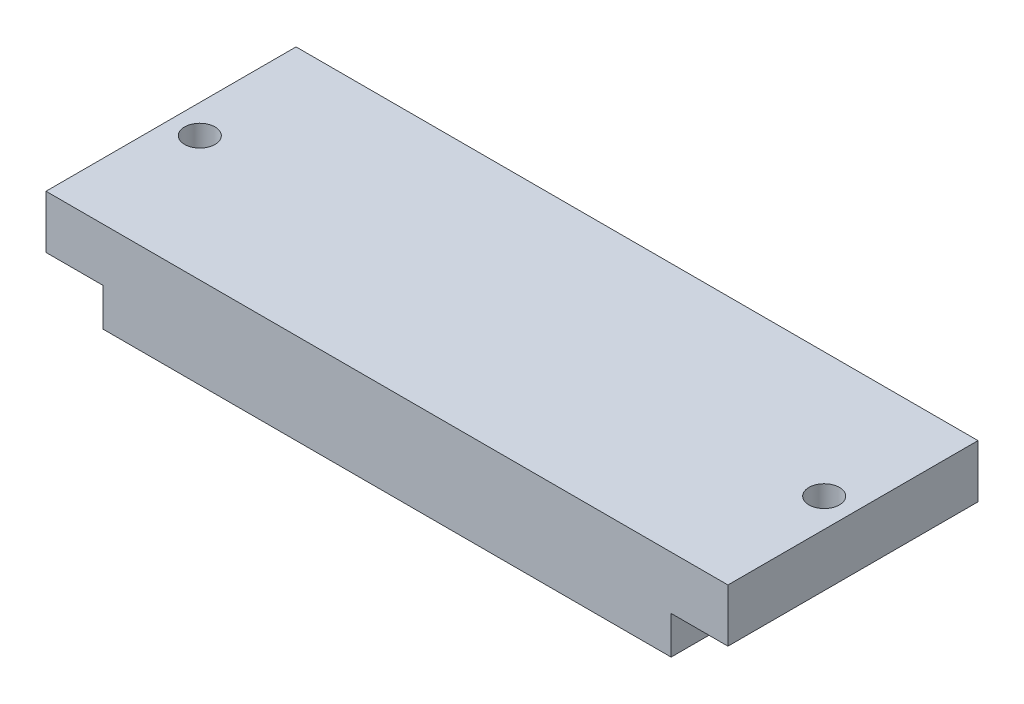
SolidWorks part; units mm, degrees
material "ABS"
ref_plane "Front Plane" through (0, 0, 0) normal (0, 0, 1) x (1, 0, 0)
ref_plane "Top Plane" through (0, 0, 0) normal (0, 1, 0) x (1, 0, 0)
ref_plane "Right Plane" through (0, 0, 0) normal (1, 0, 0) x (0, 0, -1)
sketch "Sketch1" plane through (0, 0, 0) normal (0, 0, 1) x (1, 0, 0)
  line L0 (0, 0) -> (114.3, 0)
  line L1 (0, 0) -> (0, -8.89)
  line L2 (0, -8.89) -> (9.525, -8.89)
  line L3 (114.3, 0) -> (114.3, -8.89)
  line L4 (114.3, -8.89) -> (104.775, -8.89)
  line L5 (9.525, -8.89) -> (9.525, -15.24)
  line L6 (104.775, -8.89) -> (104.775, -15.24)
  line L7 (9.525, -15.24) -> (104.775, -15.24)
  dimension "D1" = 6.35
  dimension "D2" = 8.89
  dimension "D3" = 9.525
  dimension "D4" = 95.25
extrude "Boss-Extrude1" add sketch "Sketch1" along normal blind 41.91
hole_wizard "#10 Clearance Hole1" positions "3DSketch2" profile "Sketch3" hole size "#10" standard "Ansi Inch" end condition through all
sketch3d "3DSketch2"
  line L0 (4.826, 0, 0) -> (4.826, 0, 41.91) construction
  line L1 (114.3, 0, 0) -> (0, 0, 0) construction
  line L2 (114.3, 0, 41.91) -> (0, 0, 41.91) construction
  line L3 (0, 0, 41.91) -> (0, 0, 0) construction
  line L4 (109.474, 0, 0) -> (109.474, 0, 41.91) construction
  line L5 (114.3, 0, 41.91) -> (114.3, 0, 0) construction
  line L6 (0, 0, 20.955) -> (114.3, 0, 20.955) construction
  point P0 (4.826, 0, 20.955)
  point P2 (109.474, 0, 20.955)
  dimension "D1" = 4.826
  dimension "D2" = 4.826
  dimension "D3" = 20.955
sketch "Sketch3" plane through (4.826, 0, 20.955) normal (1, 0, 0) x (0, 0, 1)
  line L0 (0, 0) -> (0, 15.24)
  line L1 (0, 15.24) -> (2.5527, 15.24)
  line L2 (2.5527, 15.24) -> (2.5527, 0)
  line L5 (2.5527, 0) -> (0, 0)
  line L11 (0, -6.35) -> (0, 107.95) construction
  dimension "Thru Hole Dia." = 5.1054
  dimension "Thru Hole Depth" = 15.24
